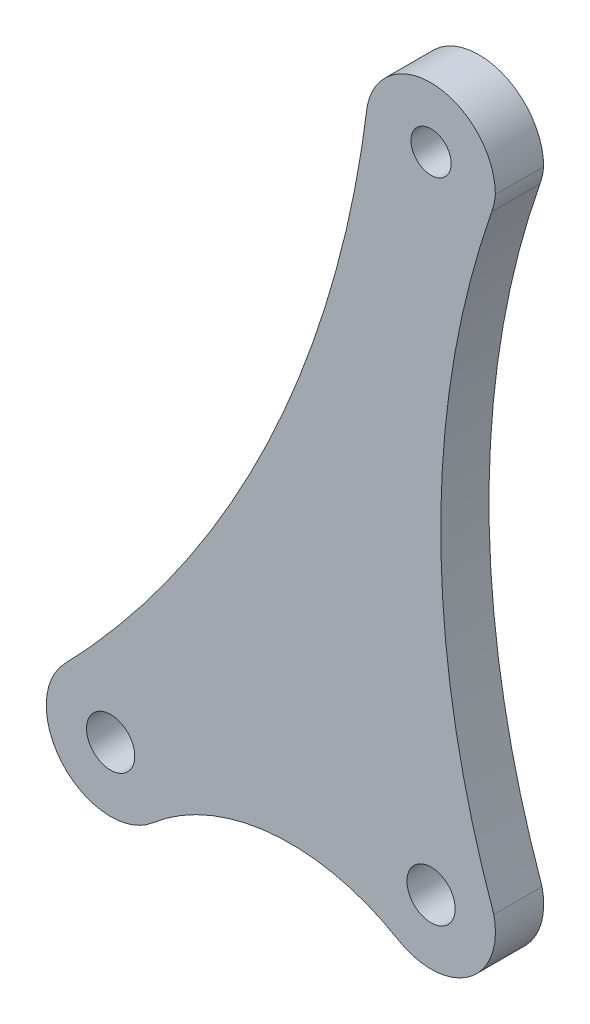
SolidWorks part; units mm, degrees
ref_plane "前基準面" through (0, 0, 0) normal (0, 0, 1) x (1, 0, 0)
ref_plane "上基準面" through (0, 0, 0) normal (0, 1, 0) x (1, 0, 0)
ref_plane "右基準面" through (0, 0, 0) normal (1, 0, 0) x (0, 0, -1)
sketch "草圖2" plane through (0, 0, 0) normal (0, 0, 1) x (1, 0, 0)
  circle A0 centre (27.9997, 140.0022) radius 1.25 construction
  circle A1 centre (8.0756, 98.2593) radius 1.5 construction
  arc A2 (31.7718, 138.6713) -> (31.9, 100.9) centre (85.362, 119.9674) ccw construction
  circle A3 centre (27.9995, 100.0022) radius 1.5 construction
  arc A4 (25.9594, 96.5616) -> (10.6821, 95.225) centre (19.252, 85.2491) ccw construction
  arc A5 (5.1993, 101.0389) -> (24.0297, 140.4909) centre (-44.3435, 148.9054) ccw construction
  circle A6 centre (27.9997, 140.0022) radius 1.25
  circle A7 centre (8.0756, 98.2593) radius 1.5
  arc A8 (31.7718, 138.6713) -> (31.9, 100.9) centre (85.362, 119.9674) ccw
  circle A9 centre (27.9995, 100.0022) radius 1.5
  arc A10 (25.9594, 96.5616) -> (10.6821, 95.225) centre (19.252, 85.2491) ccw
  arc A11 (5.1993, 101.0389) -> (24.0297, 140.4909) centre (-44.3435, 148.9054) ccw
  arc A12 (24.0297, 140.4909) -> (32.0005, 139.7176) centre (27.9768, 139.7091) cw
  arc A13 (32.0005, 139.7176) -> (31.7718, 138.6713) centre (27.5678, 140.1385) cw
  arc A14 (32.0005, 139.7176) -> (24.0297, 140.4909) centre (27.9768, 139.7091) ccw construction
  arc A15 (5.1993, 101.0389) -> (10.6821, 95.225) centre (8.0756, 98.2592) ccw
  arc A16 (31.9, 100.9) -> (25.9594, 96.5616) centre (28.001, 100.0025) cw
extrude "填料-伸長1" add sketch "草圖2" along normal blind 3
